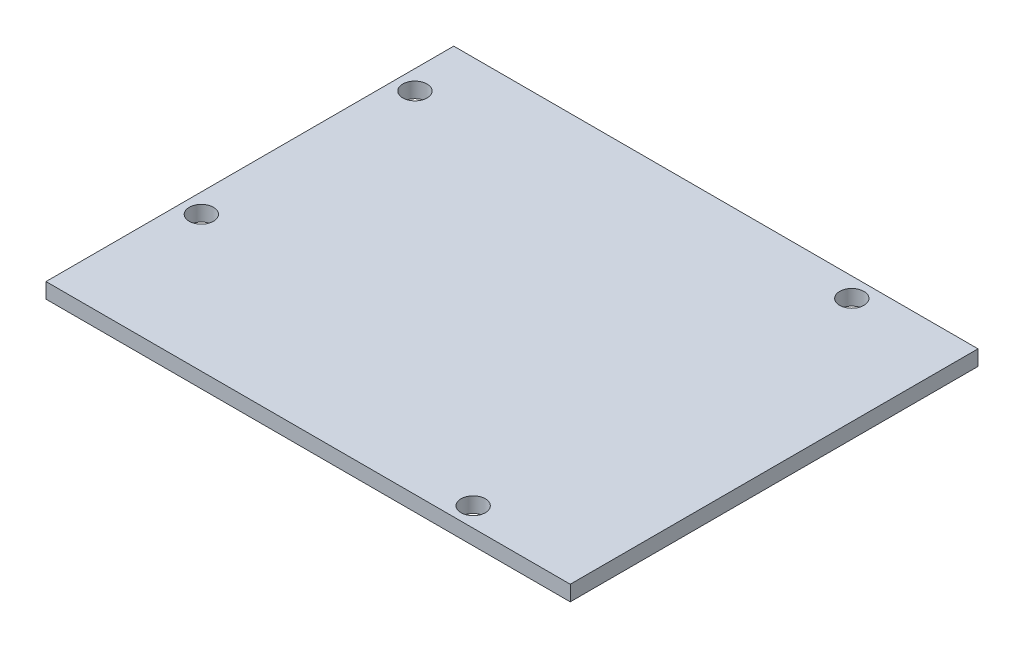
SolidWorks part; units mm, degrees
ref_plane "Front Plane" through (0, 0, 0) normal (0, 0, 1) x (1, 0, 0)
ref_plane "Top Plane" through (0, 0, 0) normal (0, 1, 0) x (1, 0, 0)
ref_plane "Right Plane" through (0, 0, 0) normal (1, 0, 0) x (0, 0, -1)
sketch "Sketch1" plane through (0, 0, 0) normal (0, 1, 0) x (1, 0, 0)
  line L1 (-0.5295, 53.1917) -> (68.0505, 53.1917)
  line L2 (-0.5295, 53.1917) -> (-0.5295, -0.1483)
  line L3 (-0.5295, -0.1483) -> (68.0505, -0.1483)
  line L4 (68.0505, 53.1917) -> (68.0505, -0.1483)
  circle A0 centre (2.0105, 17.6317) radius 1.5875
  circle A1 centre (2.0105, 45.5717) radius 1.5875
  circle A2 centre (52.8105, 2.3917) radius 1.5875
  circle A3 centre (54.0805, 50.6517) radius 1.5875
  point P12 (0, 0)
  dimension "D1" = 53.34
  dimension "D2" = 68.58
  dimension "D11" = 48.26
  dimension "D12" = 52.07
  dimension "D13" = 27.94
  dimension "D14" = 50.8
extrude "Boss-Extrude6" add sketch "Sketch1" along normal blind 2
